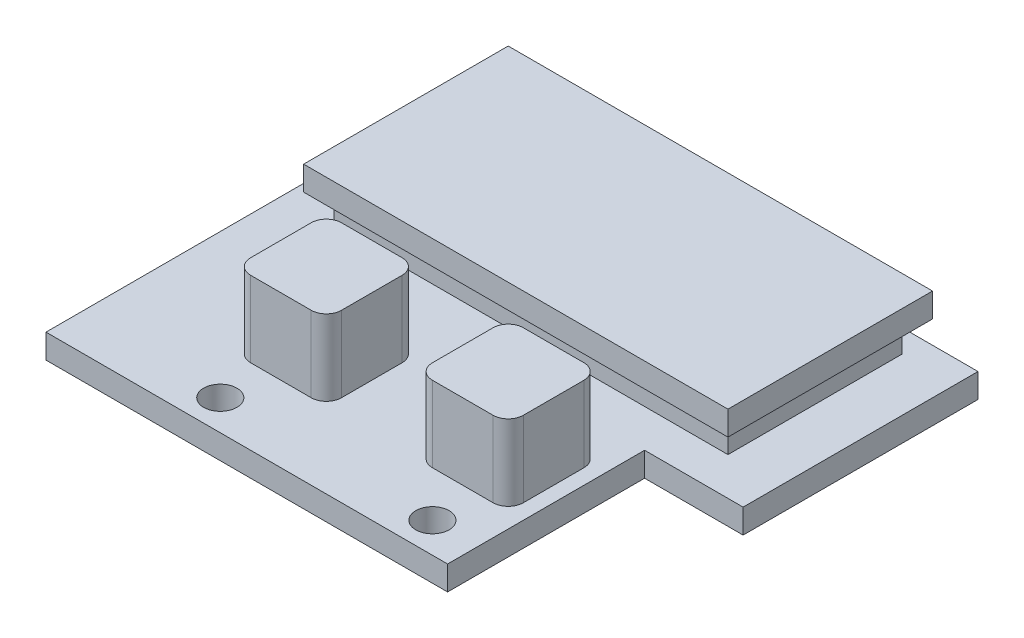
SolidWorks part; units mm, degrees
ref_plane "前视基准面" through (0, 0, 0) normal (0, 0, 1) x (1, 0, 0)
ref_plane "上视基准面" through (0, 0, 0) normal (0, 1, 0) x (1, 0, 0)
ref_plane "右视基准面" through (0, 0, 0) normal (1, 0, 0) x (0, 0, -1)
sketch "草图1" plane through (0, 0, 0) normal (0, 1, 0) x (1, 0, 0)
  line L0 (16.5, -1.25) -> (10, -1.25)
  line L1 (-16.5, -14.25) -> (10, -14.25)
  line L2 (-16.5, -14.25) -> (-16.5, 14.25)
  line L3 (-16.5, 14.25) -> (16.5, 14.25)
  line L4 (16.5, -1.25) -> (16.5, 14.25)
  line L7 (10, -1.25) -> (10, -14.25)
  point P0 (0, 0)
  point P4 (0, 14.25)
  point P10 (-16.5, 0)
  dimension "D1" = 33
  dimension "D2" = 28.5
  dimension "D3" = 15.5
  dimension "D4" = 26.5
extrude "凸台-拉伸1" add sketch "草图1" along normal blind 1.6
sketch "草图4" plane through (0, 0, 0) normal (0, -1, 0) x (1, 0, 0)
  line L0 (0, -55) -> (0, 55) construction
  line L5 (-8.5, -6) -> (-11.5, -6)
  line L6 (-8.5, -6) -> (-8.5, -12.75)
  line L7 (-8.5, -12.75) -> (-11.5, -12.75)
  line L8 (-11.5, -6) -> (-11.5, -12.75)
  line L9 (8.5, -12.75) -> (11.5, -12.75)
  line L10 (11.5, -6) -> (11.5, -12.75)
  line L11 (8.5, -6) -> (11.5, -6)
  line L12 (8.5, -6) -> (8.5, -12.75)
  line L13 (16.5, -14.25) -> (-16.5, -14.25) construction
  dimension "D1" = 3
  dimension "D2" = 6.75
  dimension "D3" = 20
  dimension "D4" = 1.5
extrude "凸台-拉伸2" add sketch "草图4" along normal blind 1.7
sketch "草图5" plane through (0, 0, 0) normal (0, -1, 0) x (-1, 0, 0)
  line L0 (0, 55) -> (0, -55) construction
  line L1 (11.5, 12.75) -> (8.5, 12.75) construction
  circle A0 centre (7, -12.25) radius 1.1
  circle A1 centre (-7, -12.25) radius 1.1
  dimension "D1" = 2.2
  dimension "D2" = 14
  dimension "D3" = 25
extrude "切除-拉伸1" cut sketch "草图5" against normal through all
sketch "草图6" plane through (0, 1.6, 0) normal (0, 1, 0) x (1, 0, 0)
  line L0 (-16.5, -14.25) -> (10, -14.25) construction
  line L1 (3, -3.25) -> (9, -3.25)
  line L2 (3, -3.25) -> (3, -9.25)
  line L3 (3, -9.25) -> (9, -9.25)
  line L4 (9, -3.25) -> (9, -9.25)
  line L5 (0, -55) -> (0, 55) construction
  line L6 (-3, -9.25) -> (-9, -9.25)
  line L7 (-9, -3.25) -> (-9, -9.25)
  line L8 (-3, -3.25) -> (-9, -3.25)
  line L9 (-3, -3.25) -> (-3, -9.25)
  dimension "D1" = 6
  dimension "D2" = 6
  dimension "D3" = 5
  dimension "D4" = 12
extrude "凸台-拉伸3" add sketch "草图6" along normal blind 5
fillet "圆角1" radius 1 8 edges at (3, 4.1, 3.25) (9, 4.1, 3.25) (9, 4.1, 9.25) (3, 4.1, 9.25) (-3, 4.1, 3.25) (-9, 4.1, 3.25) (-3, 4.1, 9.25) (-9, 4.1, 9.25)
sketch "草图7" plane through (0, 1.6, 0) normal (0, 1, 0) x (1, 0, 0)
  line L0 (16.5, 14.25) -> (-16.5, 14.25) construction
  line L1 (-14, 0.25) -> (14, 0.25)
  line L2 (-14, 0.25) -> (-14, 13.75)
  line L3 (-14, 13.75) -> (14, 13.75)
  line L4 (14, 0.25) -> (14, 13.75)
  point P4 (0, 13.75)
  dimension "D1" = 28
  dimension "D2" = 13.5
  dimension "D3" = 0.5
extrude "凸台-拉伸4" add sketch "草图7" along normal blind 1.6 from offset 2 separate body
sketch "草图8" plane through (0, 1.6, 0) normal (0, 1, 0) x (1, 0, 0)
  line L0 (-13, 12.75) -> (-13, 1.25)
  line L1 (-13, 1.25) -> (13, 1.25)
  line L2 (13, 1.25) -> (13, 12.75)
  line L3 (13, 12.75) -> (-13, 12.75)
  line L4 (-14, 13.75) -> (-14, 0.25)
  line L5 (-14, 0.25) -> (14, 0.25)
  line L6 (14, 0.25) -> (14, 13.75)
  line L7 (14, 13.75) -> (-14, 13.75)
  line L8 (-14, 13.75) -> (-14, 0.25) construction
  line L9 (-14, 0.25) -> (14, 0.25) construction
  line L10 (14, 0.25) -> (14, 13.75) construction
  line L11 (14, 13.75) -> (-14, 13.75) construction
  dimension "D1" = 0
  dimension "D2" = 1
extrude "凸台-拉伸5" add sketch "草图8" along normal up to surface (2 mm away) up to face at (0, 3.6, -7)
